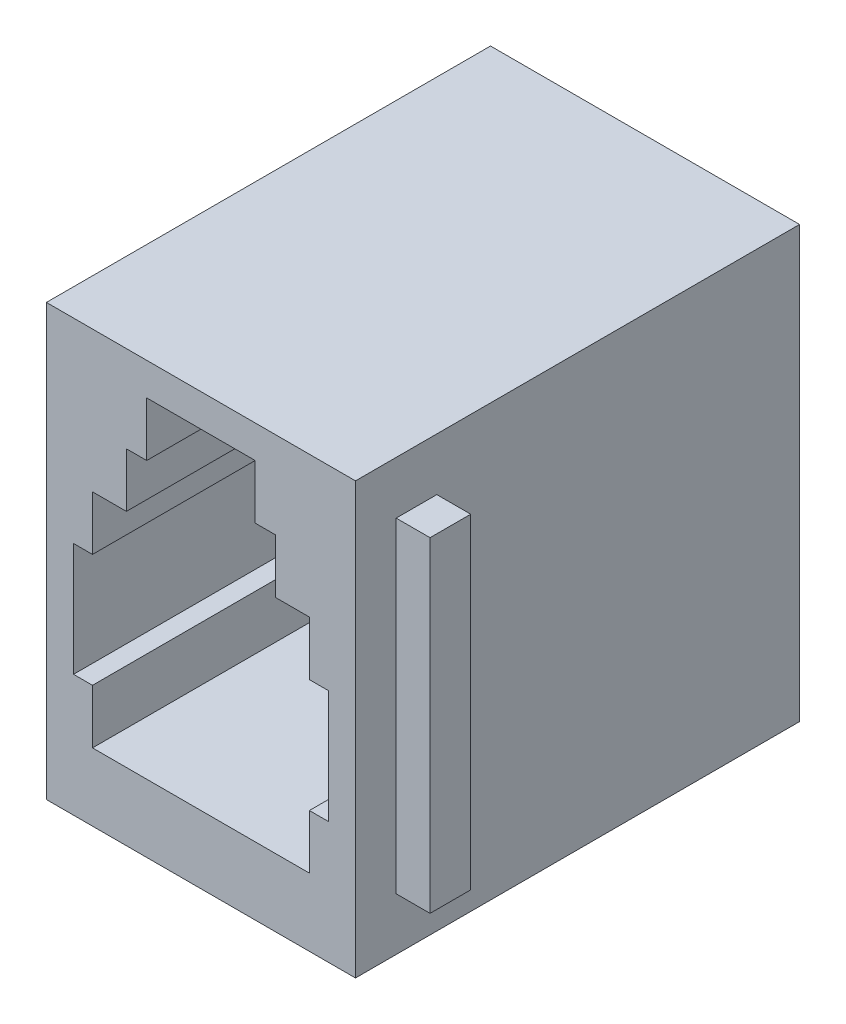
SolidWorks part; units mm, degrees
ref_plane "Front Plane" through (0, 0, 0) normal (0, 0, 1) x (1, 0, 0)
ref_plane "Top Plane" through (0, 0, 0) normal (0, 1, 0) x (1, 0, 0)
ref_plane "Right Plane" through (0, 0, 0) normal (1, 0, 0) x (0, 0, -1)
sketch "Sketch1" plane through (0, 0, 0) normal (0, 0, 1) x (1, 0, 0)
  line L0 (0, 0) -> (0, -7.94) construction
  line L1 (-5.7, 7.94) -> (5.7, 7.94)
  line L2 (-5.7, 7.94) -> (-5.7, -7.94)
  line L3 (-5.7, -7.94) -> (5.7, -7.94)
  line L4 (5.7, 7.94) -> (5.7, -7.94)
  line L5 (0, 0) -> (-5.7, 0) construction
  dimension "D1" = 15.88
  dimension "D2" = 11.4
extrude "Boss-Extrude1" add sketch "Sketch1" along normal blind 16.38
sketch "Sketch2" plane through (0, 0, 16.38) normal (0, 0, 1) x (1, 0, 0)
  line L0 (0, 0) -> (0, 6.74) construction
  line L1 (-2, 6.74) -> (2, 6.74)
  line L2 (2, 6.74) -> (2, 4.74)
  line L3 (2, 4.74) -> (2.75, 4.74)
  line L4 (2.75, 4.74) -> (2.75, 2.74)
  line L5 (2.75, 2.74) -> (4, 2.74)
  line L6 (4, 2.74) -> (4, 0.74)
  line L7 (4, 0.74) -> (4.7, 0.74)
  line L8 (4.7, 0.74) -> (4.7, -3.44)
  line L9 (4.7, -3.44) -> (4, -3.44)
  line L10 (4, -3.44) -> (4, -5.44)
  line L11 (4, -5.44) -> (-4, -5.44)
  line L12 (0, 0) -> (0, -5.44) construction
  line L13 (5.7, -7.94) -> (5.7, 7.94) construction
  line L14 (5.7, 7.94) -> (-5.7, 7.94) construction
  line L15 (-5.7, -7.94) -> (5.7, -7.94) construction
  line L16 (4, 0.74) -> (4, -3.44) construction
  line L17 (-4, -3.44) -> (-4, -5.44)
  line L18 (-4.7, -3.44) -> (-4, -3.44)
  line L19 (-4, 0.74) -> (-4.7, 0.74)
  line L20 (-4.7, 0.74) -> (-4.7, -3.44)
  line L21 (-4, 2.74) -> (-4, 0.74)
  line L22 (-2.75, 2.74) -> (-4, 2.74)
  line L23 (-2.75, 4.74) -> (-2.75, 2.74)
  line L24 (-2, 4.74) -> (-2.75, 4.74)
  line L25 (-2, 6.74) -> (-2, 4.74)
  point P8 (4.7, 1.6169)
  point P21 (4.7, 2.8427)
  point P22 (2.5785, 3.04)
  dimension "D1" = 1
  dimension "D2" = 1.2
  dimension "D3" = 2.5
  dimension "D4" = 2
  dimension "D5" = 0.7
  dimension "D6" = 2
  dimension "D7" = 4
  dimension "D8" = 5.5
extrude "Cut-Extrude1" cut sketch "Sketch2" against normal offset from surface (15.38 mm away) 1 up to face at (0, 0, 0)
sketch "Sketch3" plane through (0, 0, 0) normal (0, 1, 0) x (1, 0, 0)
  line L0 (0, 0) -> (0, -16.38) construction
  line L1 (5.7, -16.38) -> (-5.7, -16.38) construction
  line L2 (5.7, -16.38) -> (5.7, 0) construction
  line L3 (5.7, -13.38) -> (6.95, -13.38)
  line L4 (5.7, -13.38) -> (5.7, -14.88)
  line L5 (5.7, -14.88) -> (6.95, -14.88)
  line L6 (6.95, -13.38) -> (6.95, -14.88)
  line L7 (-6.95, -13.38) -> (-6.95, -14.88)
  line L8 (-5.7, -14.88) -> (-6.95, -14.88)
  line L9 (-5.7, -13.38) -> (-5.7, -14.88)
  line L10 (-5.7, -13.38) -> (-6.95, -13.38)
  dimension "D1" = 13.9
  dimension "D2" = 1.5
  dimension "D3" = 1.5
extrude "Boss-Extrude2" add sketch "Sketch3" along normal mid plane 12
